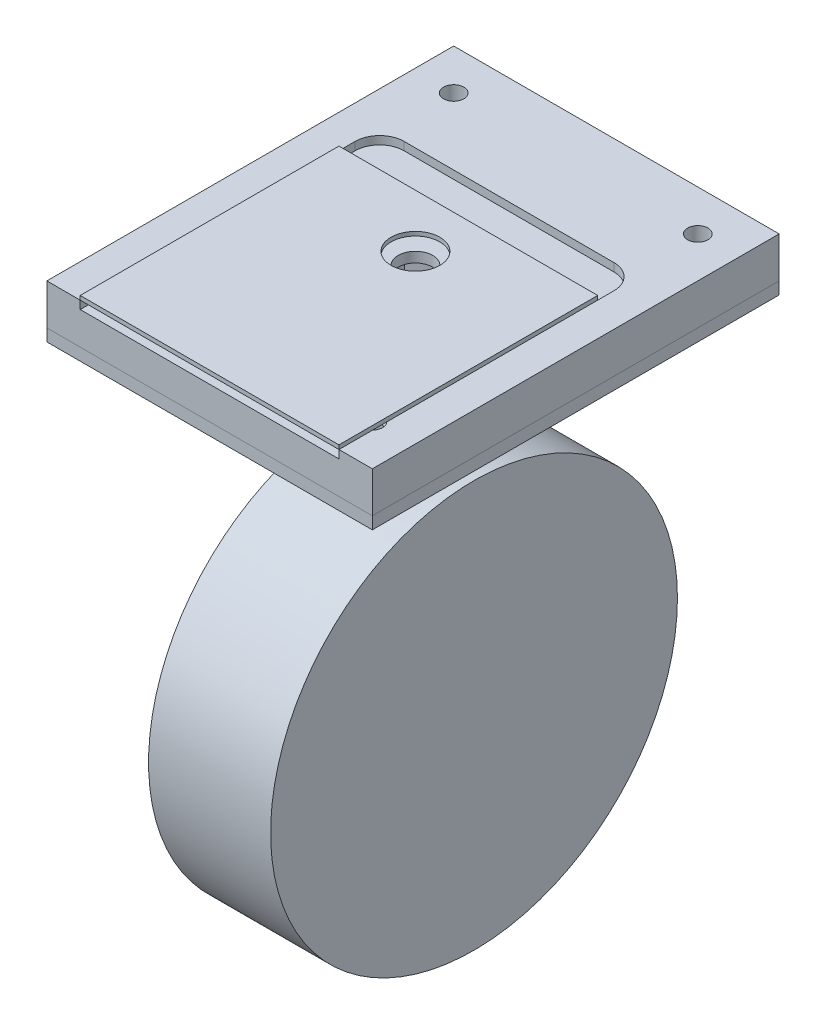
SolidWorks part; units mm, degrees
ref_plane "Front Plane" through (0, 0, 0) normal (0, 0, 1) x (1, 0, 0)
ref_plane "Top Plane" through (0, 0, 0) normal (0, 1, 0) x (1, 0, 0)
ref_plane "Right Plane" through (0, 0, 0) normal (1, 0, 0) x (0, 0, -1)
sketch "Sketch1" plane through (0, 0, 0) normal (1, 0, 0) x (0, 0, -1)
  circle A0 centre (0, 50) radius 50
  dimension "D1" = 100
extrude "Boss-Extrude1" add sketch "Sketch1" along normal mid plane 30
sketch "Sketch2" plane through (0, 0, 0) normal (0, 1, 0) x (1, 0, 0)
  line L0 (0, 0) -> (-40, 0) construction
  line L1 (-40, 50) -> (40, 50)
  line L2 (-40, 50) -> (-40, -50)
  line L3 (-40, -50) -> (40, -50)
  line L4 (40, 50) -> (40, -50)
  line L5 (0, 50) -> (0, 0) construction
  circle A0 centre (-30, 40) radius 4.75
  circle A1 centre (30, 40) radius 4.75
  circle A2 centre (-30, -40) radius 4.75
  circle A3 centre (30, -40) radius 4.75
  dimension "D9" = 9.5
  dimension "D1" = 80
  dimension "D2" = 60
  dimension "D3" = 40
  dimension "D4" = 30
  dimension "D5" = 80
  dimension "D6" = 100
extrude "Boss-Extrude2" add sketch "Sketch2" against normal blind 3 from offset 130 separate body
sketch "Sketch3" plane through (0, 130, 0) normal (0, 1, 0) x (1, 0, 0)
  line L0 (0, 0.6) -> (0, 13.6) construction
  line L1 (-31.8, 13.6) -> (31.8, 13.6)
  line L2 (-31.8, 13.6) -> (-31.8, -50)
  line L3 (-31.8, -50) -> (31.8, -50)
  line L4 (31.8, 13.6) -> (31.8, -50)
  line L5 (-40, -50) -> (40, -50) construction
  circle A0 centre (0, 0.6) radius 6
  dimension "D4" = 12
  dimension "D1" = 63.6
  dimension "D2" = 63.6
  dimension "D3" = 13
extrude "Boss-Extrude3" add sketch "Sketch3" along normal blind 3 from offset 8 separate body
sketch "Sketch4" plane through (0, 130, 0) normal (0, 1, 0) x (1, 0, 0)
  line L4 (-40, 50) -> (-40, -50)
  line L5 (-40, -50) -> (40, -50)
  line L6 (40, -50) -> (40, 50)
  line L7 (40, 50) -> (-40, 50)
  line L8 (-40, 50) -> (-40, -50)
  line L9 (-40, -50) -> (40, -50)
  line L10 (40, -50) -> (40, 50)
  line L11 (40, 50) -> (-40, 50)
  dimension "D1" = 0
extrude "Boss-Extrude4" add sketch "Sketch4" along normal blind 10 separate body
hole_wizard "M6 Tapped Hole1" positions "Sketch5" profile "Sketch6" tap size "M6" standard "ISO" end condition through all
sketch "Sketch5" plane through (0, 140, 0) normal (0, 1, 0) x (1, 0, 0)
  point P0 (-30, 40)
  point P3 (30, 40)
  point P6 (-30, -40)
  point P9 (30, -40)
cosmetic thread "Hole Thread1" parameters "D2"=6
cosmetic thread "Hole Thread2" parameters "D2"=6
cosmetic thread "Hole Thread3" parameters "D2"=6
cosmetic thread "Hole Thread4" parameters "D2"=6
sketch "Sketch6" plane through (-30, 140, -40) normal (1, 0, 0) x (0, 0, 1)
  line L0 (0, 0) -> (0, 140)
  line L1 (0, 140) -> (2.5, 140)
  line L2 (2.5, 140) -> (2.5, 0)
  line L5 (2.5, 0) -> (0, 0)
  line L11 (0, -6.35) -> (0, 107.95) construction
  dimension "Thru Tap Drill Dia." = 5
  dimension "Thru Tap Drill Depth" = 140
sketch "Sketch7" plane through (0, 140, 0) normal (0, 1, 0) x (1, 0, 0)
  circle A0 centre (0, 0.6) radius 4.25
  dimension "D1" = 8.5
extrude "Cut-Extrude1" cut sketch "Sketch7" against normal through all
sketch "Sketch8" plane through (0, 140, 0) normal (0, 1, 0) x (1, 0, 0)
  line L1 (-31.8, -50) -> (31.8, -50)
  line L2 (-31.8, -50) -> (-31.8, 17.6)
  line L3 (-25.8, 23.6) -> (25.8, 23.6)
  line L4 (31.8, -50) -> (31.8, 17.6)
  line L5 (31.8, -50) -> (31.8, 13.6) construction
  line L6 (31.8, 13.6) -> (-31.8, 13.6) construction
  arc A0 (25.8, 23.6) -> (31.8, 17.6) centre (25.8, 17.6) cw
  arc A1 (-31.8, 17.6) -> (-25.8, 23.6) centre (-25.8, 17.6) cw
  dimension "D2" = 6
  dimension "D1" = 10
extrude "Cut-Extrude2" cut sketch "Sketch8" against normal offset from surface (2 mm away) 8 up to face at (0, 130, 3.65)
sketch "Sketch9" plane through (0, 130, 0) normal (0, -1, 0) x (1, 0, 0)
  line L1 (0, 6.7901) -> (-6.4, 3.095)
  line L2 (-6.4, 3.095) -> (-6.4, -4.295)
  line L3 (-6.4, -4.295) -> (0, -7.9901)
  line L4 (0, -7.9901) -> (6.4, -4.295)
  line L5 (6.4, -4.295) -> (6.4, 3.095)
  line L6 (6.4, 3.095) -> (0, 6.7901)
  circle A0 centre (0, -0.6) radius 6.4 construction
  dimension "D1" = 12.8
extrude "Cut-Extrude3" cut sketch "Sketch9" against normal blind 5.5
